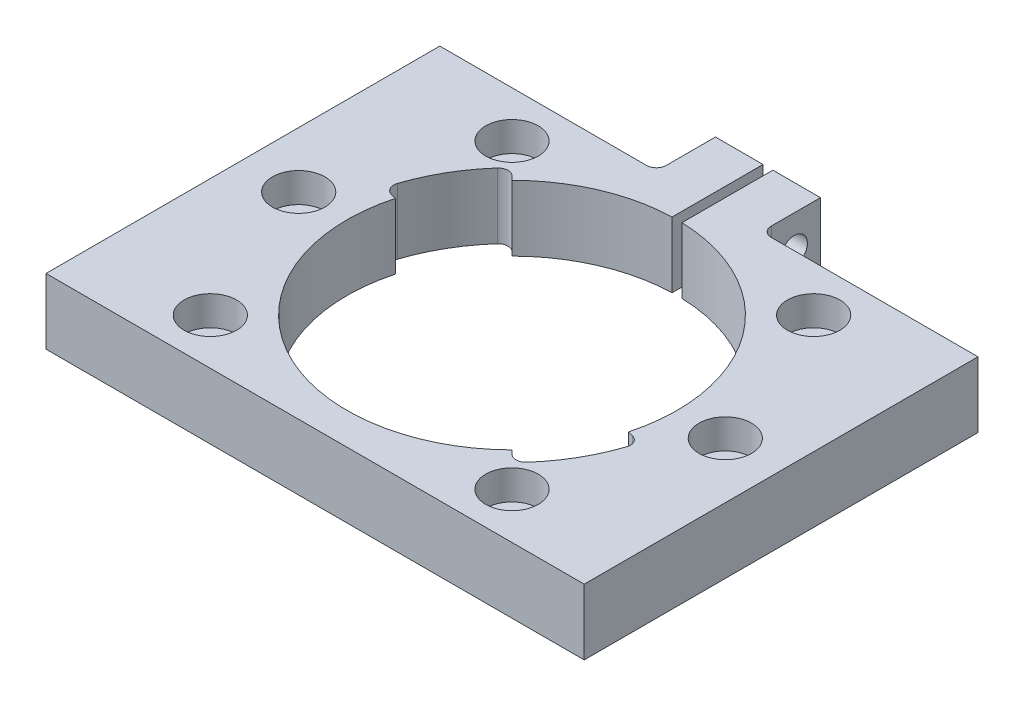
SolidWorks part; units mm, degrees
material "6061 Alloy"
ref_plane "Front Plane" through (0, 0, 0) normal (0, 0, 1) x (1, 0, 0)
ref_plane "Top Plane" through (0, 0, 0) normal (0, 1, 0) x (1, 0, 0)
ref_plane "Right Plane" through (0, 0, 0) normal (1, 0, 0) x (0, 0, -1)
sketch "Sketch1" plane through (0, 76, 0) normal (0, 1, 0) x (1, 0, 0)
  line L0 (-18.3542, 18.3542) -> (18.3542, -18.3542)
  line L1 (-41, -30) -> (41, -30)
  line L2 (-41, -30) -> (-41, 30)
  line L3 (-41, 30) -> (41, 30)
  line L4 (41, -30) -> (41, 30)
  line L5 (-41, -30) -> (41, 30) construction
  line L6 (-41, 30) -> (41, -30) construction
  line L7 (-25.0722, 6.7181) -> (25.0722, -6.7181)
  line L8 (-103.759, 0) -> (103.759, 0) construction
  circle A0 centre (0, 0) radius 25.15
  arc A1 (-20.5349, 18.2912) -> (-26.1081, 8.6381) centre (0, 0) ccw
  arc A2 (26.1081, -8.6381) -> (20.5349, -18.2912) centre (0, 0) cw
  circle A3 centre (0, 0) radius 27.5 construction
  arc A4 (18.3542, -18.3542) -> (20.5349, -18.2912) centre (19.4148, -17.2935) ccw
  arc A5 (25.0722, -6.7181) -> (26.1081, -8.6381) centre (24.684, -8.167) cw
  arc A6 (-25.0722, 6.7181) -> (-26.1081, 8.6381) centre (-24.684, 8.167) cw
  arc A7 (-18.3542, 18.3542) -> (-20.5349, 18.2912) centre (-19.4148, 17.2935) ccw
  circle A8 centre (22.981, 22.981) radius 2 construction
  circle A9 centre (32.5, 0) radius 2 construction
  circle A10 centre (22.981, -22.981) radius 2 construction
  circle A11 centre (-22.981, -22.981) radius 2 construction
  circle A12 centre (-32.5, 0) radius 2 construction
  circle A13 centre (-22.981, 22.981) radius 2 construction
  circle A14 centre (22.981, 22.981) radius 2
  circle A15 centre (32.5, 0) radius 2
  circle A16 centre (22.981, -22.981) radius 2
  circle A17 centre (-22.981, -22.981) radius 2
  circle A18 centre (-32.5, 0) radius 2
  circle A19 centre (-22.981, 22.981) radius 2
  point P0 (0, 0)
  dimension "D1" = 50.3
  dimension "D4" = 1.5
  dimension "D2" = 45
  dimension "D3" = 15
  dimension "D5" = 82
  dimension "D6" = 60
extrude "Boss-Extrude1" add sketch "Sketch1" along normal blind 10 contours L1 L4 L3 L2 A19 A18 A17 A16 A15 A14 A7 L0 A0 L7 A5 A2 A4 A6 A1
sketch "Sketch2" plane through (0, 86, 0) normal (0, 1, 0) x (1, 0, 0)
  line L0 (0, -142.3844) -> (0, 142.3844) construction
  line L1 (-8, 39) -> (8, 39)
  line L2 (-8, 39) -> (-8, 30)
  line L3 (-8, 30) -> (8, 30)
  line L4 (8, 39) -> (8, 30)
  line L5 (-8, 39) -> (8, 30) construction
  line L6 (-8, 30) -> (8, 39) construction
  line L7 (-41, 30) -> (41, 30) construction
  point P0 (0, 34.5)
  dimension "D1" = 9
  dimension "D2" = 16
extrude "Boss-Extrude2" add sketch "Sketch2" against normal blind 10
sketch "Sketch3" plane through (0, 86, 0) normal (0, 1, 0) x (1, 0, 0)
  line L0 (0, -142.3844) -> (0, 142.3844) construction
  line L1 (-0.75, 25) -> (0.75, 25)
  line L2 (-0.75, 25) -> (-0.75, 39)
  line L3 (-0.75, 39) -> (0.75, 39)
  line L4 (0.75, 25) -> (0.75, 39)
  line L5 (-0.75, 25) -> (0.75, 39) construction
  line L6 (-0.75, 39) -> (0.75, 25) construction
  line L7 (8, 39) -> (-8, 39) construction
  point P0 (0, 32)
  dimension "D1" = 14
  dimension "D2" = 1.5
extrude "Cut-Extrude1" cut sketch "Sketch3" against normal blind 10
sketch "Sketch4" plane through (8, 0, 0) normal (1, 0, 0) x (0, 0, -1)
  line L0 (35, 81) -> (39, 81) construction
  line L1 (39, 76) -> (39, 86) construction
  circle A0 centre (35, 81) radius 2
  dimension "D1" = 4
  dimension "D2" = 4
extrude "Cut-Extrude2" cut sketch "Sketch4" against normal up to vertex (7.25 mm away)
sketch "Sketch5" plane through (-0.75, 0, 0) normal (1, 0, 0) x (0, 0, -1)
  circle A0 centre (35, 81) radius 1.6
  dimension "D1" = 3.2
extrude "Cut-Extrude3" cut sketch "Sketch5" against normal blind 10
sketch "Sketch7" plane through (0, 86, 0) normal (0, 1, 0) x (1, 0, 0)
  circle A0 centre (-22.981, 22.981) radius 4
  circle A1 centre (22.981, 22.981) radius 4
  circle A2 centre (32.5, 0) radius 4
  circle A3 centre (-32.5, 0) radius 4
  circle A4 centre (-22.981, -22.981) radius 4
  circle A5 centre (22.981, -22.981) radius 4
  dimension "D1" = 8
extrude "Cut-Extrude4" cut sketch "Sketch7" against normal blind 4.5
fillet "Fillet1" radius 1.5 2 edges at (-8, 81, -30) (8, 81, -30)
